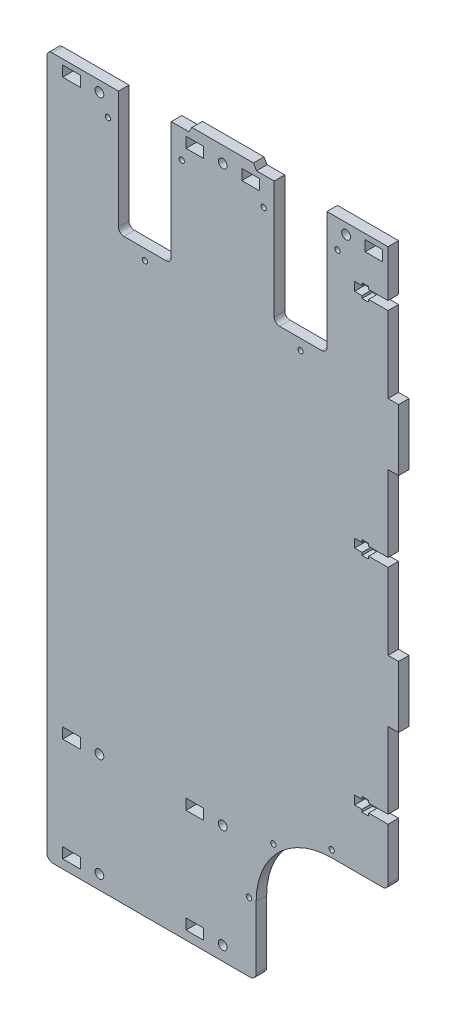
SolidWorks part; units mm, degrees
ref_plane "Спереди" through (0, 0, 0) normal (0, 0, 1) x (1, 0, 0)
ref_plane "Сверху" through (0, 0, 0) normal (0, 1, 0) x (1, 0, 0)
ref_plane "Справа" through (0, 0, 0) normal (1, 0, 0) x (0, 0, -1)
sketch "Эскиз1" plane through (0, 0, 0) normal (0, 0, 1) x (1, 0, 0)
  line L0 (94, -65.75) -> (94, -22.45)
  line L1 (94, -22.45) -> (83, -22.45)
  line L2 (83, -22.45) -> (83, -23.925)
  line L3 (83, -23.925) -> (79.2, -23.925)
  line L4 (79.2, -23.925) -> (79.2, -22.45)
  line L5 (79.2, -22.45) -> (75, -22.45)
  line L6 (75, -22.45) -> (75, -17.55)
  line L7 (108.7302, -20) -> (68.1024, -20) construction
  line L8 (79.2, -17.55) -> (75, -17.55)
  line L9 (79.2, -16.075) -> (79.2, -17.55)
  line L10 (83, -16.075) -> (79.2, -16.075)
  line L11 (83, -17.55) -> (83, -16.075)
  line L12 (94, -17.55) -> (83, -17.55)
  line L13 (94, -17.55) -> (94, 9)
  line L14 (94, -148.95) -> (83, -148.95)
  line L15 (83, -148.95) -> (83, -150.425)
  line L32 (83, -150.425) -> (79.2, -150.425)
  line L33 (79.2, -150.425) -> (79.2, -148.95)
  line L34 (79.2, -148.95) -> (75, -148.95)
  line L35 (75, -144.05) -> (75, -148.95)
  line L36 (10.8625, 0) -> (20.8625, 0) construction
  line L37 (20.8625, 0) -> (20.8625, 6) construction
  line L38 (20.8625, 6) -> (10.8625, 6) construction
  line L39 (10.8625, 6) -> (10.8625, 0) construction
  line L40 (-20.8625, 0) -> (-10.8625, 0) construction
  line L41 (-10.8625, 0) -> (-10.8625, 6) construction
  line L42 (-10.8625, 6) -> (-20.8625, 6) construction
  line L43 (-20.8625, 6) -> (-20.8625, 0) construction
  line L44 (79.2, -144.05) -> (75, -144.05)
  line L45 (79.2, -142.575) -> (79.2, -144.05)
  line L46 (83, -142.575) -> (79.2, -142.575)
  line L47 (83, -144.05) -> (83, -142.575)
  line L52 (10.8625, 0) -> (20.8625, 0)
  line L53 (20.8625, 0) -> (20.8625, 6)
  line L54 (20.8625, 6) -> (10.8625, 6)
  line L55 (10.8625, 6) -> (10.8625, 0)
  line L56 (-20.8625, 0) -> (-10.8625, 0)
  line L57 (-10.8625, 0) -> (-10.8625, 6)
  line L58 (-10.8625, 6) -> (-20.8625, 6)
  line L59 (-20.8625, 6) -> (-20.8625, 0)
  line L64 (-72.5875, 3) -> (-67.6875, 3) construction
  line L65 (-72.5875, 6) -> (-72.5875, 0) construction
  line L66 (-67.6875, 6) -> (-67.6875, 0) construction
  line L67 (-2.45, 3) -> (2.45, 3) construction
  line L68 (-2.45, 6) -> (-2.45, 0) construction
  line L69 (2.45, 6) -> (2.45, 0) construction
  line L70 (0, 0) -> (0, 50000) construction
  line L71 (-59.275, 9) -> (-59.275, -61)
  line L72 (-59.275, -61) -> (-29.275, -61)
  line L73 (-29.275, -61) -> (-29.275, 9)
  line L74 (-29.275, 9) -> (29.275, 9) construction
  line L75 (-59.275, 9) -> (-100, 9)
  line L76 (-100, 9) -> (-100, -390)
  line L77 (-100, 0) -> (-100, 6) construction
  line L78 (29.275, -61) -> (29.275, 9)
  line L79 (-91, 0) -> (-81, 0) construction
  line L80 (59.275, -61) -> (29.275, -61)
  line L81 (59.275, 9) -> (59.275, -61)
  line L82 (59.275, 9) -> (94, 9)
  line L83 (-81, 0) -> (-81, 6) construction
  line L84 (-81, 6) -> (-91, 6) construction
  line L85 (-91, 6) -> (-91, 0) construction
  line L86 (81, 0) -> (91, 0) construction
  line L87 (91, 0) -> (91, 6) construction
  line L88 (91, 6) -> (81, 6) construction
  line L89 (81, 6) -> (81, 0) construction
  line L90 (-91, 0) -> (-81, 0)
  line L91 (-81, 0) -> (-81, 6)
  line L92 (-81, 6) -> (-91, 6)
  line L93 (-91, 6) -> (-91, 0)
  line L94 (81, 0) -> (91, 0)
  line L95 (91, 0) -> (91, 6)
  line L96 (91, 6) -> (81, 6)
  line L97 (81, 6) -> (81, 0)
  line L98 (94, 9) -> (94, -65.75) construction
  line L99 (100, 15.7119) -> (100, -49984.2881) construction
  line L100 (100, 6) -> (100, 0) construction
  line L101 (94, -65.75) -> (100, -65.75)
  line L102 (100, -65.75) -> (100, -100.75)
  line L103 (100, -100.75) -> (94, -100.75)
  line L104 (-100, -390) -> (100, -390) construction
  line L105 (-100, -390) -> (19, -390)
  line L106 (19, -390) -> (19, -351)
  line L107 (62, -308) -> (94, -308)
  line L108 (94, -308) -> (94, -227.25) construction
  line L109 (94, -227.25) -> (100, -227.25)
  line L110 (100, -227.25) -> (100, -192.25)
  line L111 (100, -192.25) -> (94, -192.25)
  line L112 (94, -192.25) -> (94, -100.75) construction
  line L113 (-67.6875, 3) -> (-59.275, 3) construction
  line L114 (-29.275, 3) -> (-20.8625, 3) construction
  line L115 (94, 6) -> (94, 0) construction
  line L132 (-91, -385) -> (-81, -385)
  line L133 (-81, -385) -> (-81, -379)
  line L134 (-81, -379) -> (-91, -379)
  line L135 (-91, -379) -> (-91, -385)
  line L136 (-20.8625, -385) -> (-10.8625, -385)
  line L137 (-10.8625, -385) -> (-10.8625, -379)
  line L138 (-10.8625, -379) -> (-20.8625, -379)
  line L139 (-20.8625, -379) -> (-20.8625, -385)
  line L140 (-91, -326) -> (-81, -326)
  line L141 (-81, -326) -> (-81, -320)
  line L142 (-81, -320) -> (-91, -320)
  line L143 (-91, -320) -> (-91, -326)
  line L144 (-20.8625, -326) -> (-10.8625, -326)
  line L145 (-10.8625, -326) -> (-10.8625, -320)
  line L146 (-10.8625, -320) -> (-20.8625, -320)
  line L147 (-20.8625, -320) -> (-20.8625, -326)
  line L148 (-91, -385) -> (-91, -326) construction
  line L149 (11, -390) -> (11, -351) construction
  line L150 (62, -300) -> (94, -300) construction
  line L151 (100, -326) -> (-100, -326) construction
  line L152 (-29.275, 9) -> (-19.2321, 9)
  line L153 (-19.2321, 9) -> (-17.5, 12)
  line L154 (-17.5, 12) -> (17.5, 12)
  line L155 (19.2321, 9) -> (17.5, 12)
  line L156 (29.275, 9) -> (19.2321, 9)
  line L157 (94, -144.05) -> (83, -144.05)
  line L158 (104.9768, -83.25) -> (79.059, -83.25) construction
  line L159 (114.931, -209.75) -> (68.1024, -209.75) construction
  line L160 (94, -275.45) -> (83, -275.45)
  line L161 (83, -275.45) -> (83, -276.925)
  line L162 (83, -276.925) -> (79.2, -276.925)
  line L163 (79.2, -276.925) -> (79.2, -275.45)
  line L164 (79.2, -275.45) -> (75, -275.45)
  line L165 (75, -275.45) -> (75, -270.55)
  line L166 (79.2, -270.55) -> (75, -270.55)
  line L167 (79.2, -269.075) -> (79.2, -270.55)
  line L168 (83, -269.075) -> (79.2, -269.075)
  line L169 (83, -270.55) -> (83, -269.075)
  line L170 (94, -270.55) -> (83, -270.55)
  line L171 (94, -308) -> (94, -275.45)
  line L172 (94, -270.55) -> (94, -227.25)
  line L173 (94, -192.25) -> (94, -148.95)
  line L174 (94, -144.05) -> (94, -100.75)
  line L175 (70.1375, -273) -> (104.9768, -273) construction
  line L176 (70.1375, -146.5) -> (110.6164, -146.5) construction
  line L177 (-44.275, 15.1223) -> (-44.275, -83.25) construction
  line L178 (-67.6875, 0) -> (-20.8625, 0) construction
  circle A0 centre (-70.1375, 3) radius 2.5
  circle A1 centre (0, 3) radius 2.5
  circle A2 centre (70.1375, 3) radius 2.5
  arc A3 (19, -351) -> (62, -308) centre (62, -351) cw
  circle A4 centre (62, -351) radius 38 construction
  circle A9 centre (-70.1375, -382) radius 2.5
  circle A10 centre (0, -382) radius 2.5
  circle A11 centre (-70.1375, -323) radius 2.5
  circle A12 centre (0, -323) radius 2.5
  arc A13 (11, -351) -> (62, -300) centre (62, -351) cw construction
  circle A14 centre (62, -351) radius 6 construction
  circle A15 centre (-44.275, -67) radius 1.5
  circle A16 centre (-65.275, -7) radius 1.5
  circle A17 centre (-23.275, -7) radius 1.5
  circle A18 centre (44.275, -67) radius 1.5
  circle A19 centre (23.275, -7) radius 1.5
  circle A20 centre (65.275, -7) radius 1.5
  point P118 (83, -16.8125)
  point P127 (100, -83.25)
  point P140 (100, -209.75)
  point P157 (-86, 0)
  point P168 (-44.275, -61)
  dimension "D1" = 5
  dimension "D3" = 76
  dimension "D4" = 5
  dimension "D15" = 12
  dimension "D28" = 3
  dimension "D2" = 3
  dimension "D5" = 70
  dimension "D6" = 30
  dimension "D7" = 2
  dimension "D9" = 2
  dimension "D8" = 5
  dimension "D10" = 8
  dimension "D11" = 60
  dimension "D12" = 300
  dimension "D13" = 20
  dimension "D14" = 39
  dimension "D16" = 35
  dimension "D17" = 3
  dimension "D18" = 35
  dimension "D19" = 25
  dimension "D20" = 3.8
  dimension "D21" = 4.9
  dimension "D22" = 7.85
  dimension "D23" = 17
  dimension "D24" = 20
  dimension "D25" = 35
  dimension "D26" = 42
  dimension "D27" = 60
  dimension "D29" = 6
  dimension "D30" = 7
  dimension "D31" = 6
extrude "Бобышка-Вытянуть1" add sketch "Эскиз1" along normal blind 6
fillet "Скругление1" radius 3.5 2 edges at (19, -390, 3) (-100, -390, 3)
fillet "Скругление2" radius 3 6 edges at (-100, 9, 3) (29.275, -61, 3) (59.275, -61, 3) (-29.275, -61, 3) (-59.275, -61, 3) (94, -308, 3)
sketch "Эскиз2" plane through (0, 0, 6) normal (0, 0, 1) x (1, 0, 0)
  line L0 (62, -351) -> (15, -351) construction
  line L1 (62, -351) -> (28.766, -317.766) construction
  circle A0 centre (15, -351) radius 1.5
  circle A1 centre (28.766, -317.766) radius 1.5
  circle A2 centre (62, -304) radius 1.5
  point P3 (62, -351)
  dimension "D1" = 3
  dimension "D3" = 45
  dimension "D2" = 3
extrude "Вырез-Вытянуть1" cut sketch "Эскиз2" against normal through all both and the other way through all
